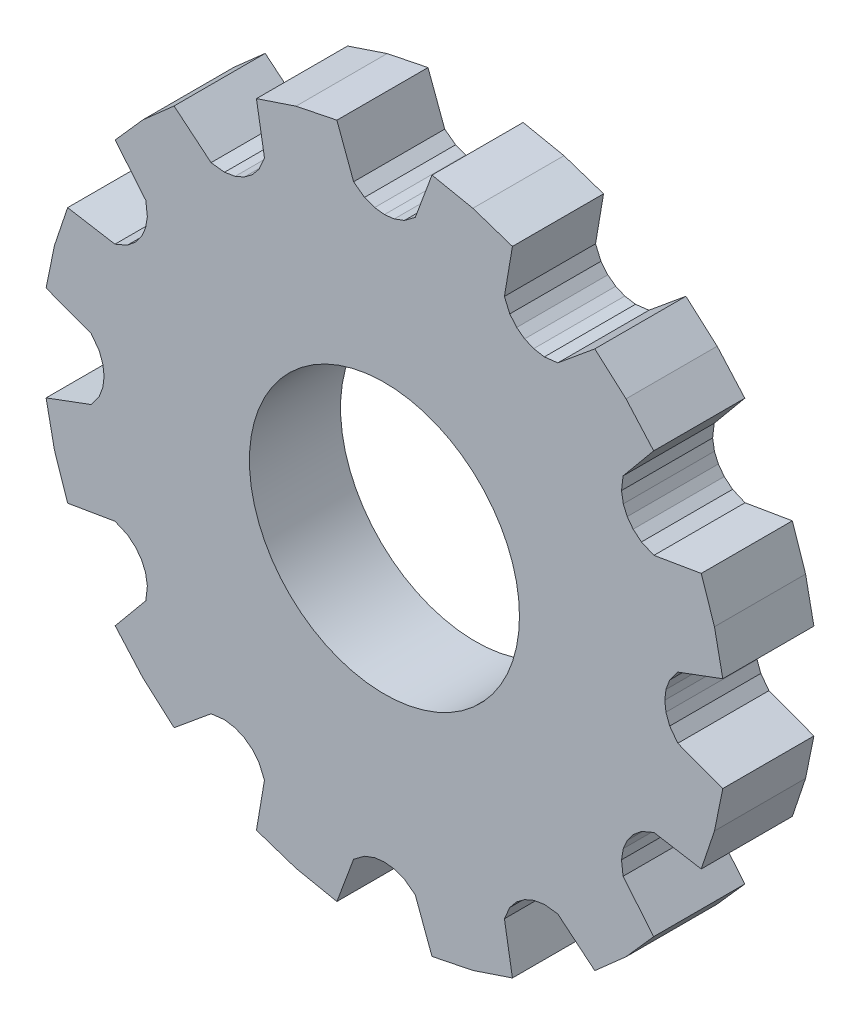
SolidWorks part; units mm, degrees
ref_plane "前视基准面" through (0, 0, 0) normal (0, 0, 1) x (1, 0, 0)
ref_plane "上视基准面" through (0, 0, 0) normal (0, 1, 0) x (1, 0, 0)
ref_plane "右视基准面" through (0, 0, 0) normal (1, 0, 0) x (0, 0, -1)
other "Configuration Table"
sketch "草图1" plane through (0, 0, 0) normal (0, 0, 1) x (1, 0, 0)
  line L0 (19.9192, -5.3373) -> (20.4212, -2.87)
  line L1 (20.4212, -2.87) -> (17.7062, -1.861)
  line L2 (17.7062, -1.861) -> (17.2174, -1.204)
  line L3 (17.2174, -1.204) -> (16.9905, -0.5933)
  line L4 (16.9905, -0.5933) -> (16.9219, 0)
  line L5 (16.9219, 0) -> (16.9905, 0.5933)
  line L6 (16.9905, 0.5933) -> (17.2174, 1.204)
  line L7 (17.2174, 1.204) -> (17.7062, 1.861)
  line L8 (17.7062, 1.861) -> (20.4212, 2.87)
  line L9 (20.4212, 2.87) -> (19.9192, 5.3373)
  line L10 (19.9192, 5.3373) -> (19.1203, 7.7251)
  line L11 (19.1203, 7.7251) -> (16.2645, 7.2414)
  line L12 (16.2645, 7.2414) -> (15.5127, 7.5661)
  line L13 (15.5127, 7.5661) -> (15.0108, 7.9814)
  line L14 (15.0108, 7.9814) -> (14.6548, 8.4609)
  line L15 (14.6548, 8.4609) -> (14.4175, 9.0091)
  line L16 (14.4175, 9.0091) -> (14.3087, 9.6514)
  line L17 (14.3087, 9.6514) -> (14.4035, 10.4648)
  line L18 (14.4035, 10.4648) -> (16.2503, 12.6961)
  line L19 (16.2503, 12.6961) -> (14.5819, 14.5819)
  line L20 (14.5819, 14.5819) -> (12.6961, 16.2503)
  line L21 (12.6961, 16.2503) -> (10.4648, 14.4035)
  line L22 (10.4648, 14.4035) -> (9.6514, 14.3087)
  line L23 (9.6514, 14.3087) -> (9.0091, 14.4175)
  line L24 (9.0091, 14.4175) -> (8.4609, 14.6548)
  line L25 (8.4609, 14.6548) -> (7.9814, 15.0108)
  line L26 (7.9814, 15.0108) -> (7.5661, 15.5127)
  line L27 (7.5661, 15.5127) -> (7.2414, 16.2645)
  line L28 (7.2414, 16.2645) -> (7.7251, 19.1203)
  line L29 (7.7251, 19.1203) -> (5.3373, 19.9192)
  line L30 (5.3373, 19.9192) -> (2.87, 20.4212)
  line L31 (2.87, 20.4212) -> (1.861, 17.7062)
  line L32 (1.861, 17.7062) -> (1.204, 17.2174)
  line L33 (1.204, 17.2174) -> (0.5933, 16.9905)
  line L34 (0.5933, 16.9905) -> (0, 16.9219)
  line L35 (0, 16.9219) -> (-0.5933, 16.9905)
  line L36 (-0.5933, 16.9905) -> (-1.204, 17.2174)
  line L37 (-1.204, 17.2174) -> (-1.861, 17.7062)
  line L38 (-1.861, 17.7062) -> (-2.87, 20.4212)
  line L39 (-2.87, 20.4212) -> (-5.3373, 19.9192)
  line L40 (-5.3373, 19.9192) -> (-7.7251, 19.1203)
  line L41 (-7.7251, 19.1203) -> (-7.2414, 16.2645)
  line L42 (-7.2414, 16.2645) -> (-7.5661, 15.5127)
  line L43 (-7.5661, 15.5127) -> (-7.9814, 15.0108)
  line L44 (-7.9814, 15.0108) -> (-8.4609, 14.6548)
  line L45 (-8.4609, 14.6548) -> (-9.0091, 14.4175)
  line L46 (-9.0091, 14.4175) -> (-9.6514, 14.3087)
  line L47 (-9.6514, 14.3087) -> (-10.4648, 14.4035)
  line L48 (-10.4648, 14.4035) -> (-12.6961, 16.2503)
  line L49 (-12.6961, 16.2503) -> (-14.5819, 14.5819)
  line L50 (-14.5819, 14.5819) -> (-16.2503, 12.6961)
  line L51 (-16.2503, 12.6961) -> (-14.4035, 10.4648)
  line L52 (-14.4035, 10.4648) -> (-14.3087, 9.6514)
  line L53 (-14.3087, 9.6514) -> (-14.4175, 9.0091)
  line L54 (-14.4175, 9.0091) -> (-14.6548, 8.4609)
  line L55 (-14.6548, 8.4609) -> (-15.0108, 7.9814)
  line L56 (-15.0108, 7.9814) -> (-15.5127, 7.5661)
  line L57 (-15.5127, 7.5661) -> (-16.2645, 7.2414)
  line L58 (-16.2645, 7.2414) -> (-19.1203, 7.7251)
  line L59 (-19.1203, 7.7251) -> (-19.9192, 5.3373)
  line L60 (-19.9192, 5.3373) -> (-20.4212, 2.87)
  line L61 (-20.4212, 2.87) -> (-17.7062, 1.861)
  line L62 (-17.7062, 1.861) -> (-17.2174, 1.204)
  line L63 (-17.2174, 1.204) -> (-16.9905, 0.5933)
  line L64 (-16.9905, 0.5933) -> (-16.9219, 0)
  line L65 (-16.9219, 0) -> (-16.9905, -0.5933)
  line L66 (-16.9905, -0.5933) -> (-17.2174, -1.204)
  line L67 (-17.2174, -1.204) -> (-17.7062, -1.861)
  line L68 (-17.7062, -1.861) -> (-20.4212, -2.87)
  line L69 (-20.4212, -2.87) -> (-19.9192, -5.3373)
  line L70 (-19.9192, -5.3373) -> (-19.1203, -7.7251)
  line L71 (-19.1203, -7.7251) -> (-16.2645, -7.2414)
  line L72 (-16.2645, -7.2414) -> (-15.5127, -7.5661)
  line L73 (-15.5127, -7.5661) -> (-15.0108, -7.9814)
  line L74 (-15.0108, -7.9814) -> (-14.6548, -8.4609)
  line L75 (-14.6548, -8.4609) -> (-14.4175, -9.0091)
  line L76 (-14.4175, -9.0091) -> (-14.3087, -9.6514)
  line L77 (-14.3087, -9.6514) -> (-14.4035, -10.4648)
  line L78 (-14.4035, -10.4648) -> (-16.2503, -12.6961)
  line L79 (-16.2503, -12.6961) -> (-14.5819, -14.5819)
  line L80 (-14.5819, -14.5819) -> (-12.6961, -16.2503)
  line L81 (-12.6961, -16.2503) -> (-10.4648, -14.4035)
  line L82 (-10.4648, -14.4035) -> (-9.6514, -14.3087)
  line L83 (-9.6514, -14.3087) -> (-9.0091, -14.4175)
  line L84 (-9.0091, -14.4175) -> (-8.4609, -14.6548)
  line L85 (-8.4609, -14.6548) -> (-7.9814, -15.0108)
  line L86 (-7.9814, -15.0108) -> (-7.5661, -15.5127)
  line L87 (-7.5661, -15.5127) -> (-7.2414, -16.2645)
  line L88 (-7.2414, -16.2645) -> (-7.7251, -19.1203)
  line L89 (-7.7251, -19.1203) -> (-5.3373, -19.9192)
  line L90 (-5.3373, -19.9192) -> (-2.87, -20.4212)
  line L91 (-2.87, -20.4212) -> (-1.861, -17.7062)
  line L92 (-1.861, -17.7062) -> (-1.204, -17.2174)
  line L93 (-1.204, -17.2174) -> (-0.5933, -16.9905)
  line L94 (-0.5933, -16.9905) -> (0, -16.9219)
  line L95 (0, -16.9219) -> (0.5933, -16.9905)
  line L96 (0.5933, -16.9905) -> (1.204, -17.2174)
  line L97 (1.204, -17.2174) -> (1.861, -17.7062)
  line L98 (1.861, -17.7062) -> (2.87, -20.4212)
  line L99 (2.87, -20.4212) -> (5.3373, -19.9192)
  line L100 (5.3373, -19.9192) -> (7.7251, -19.1203)
  line L101 (7.7251, -19.1203) -> (7.2414, -16.2645)
  line L102 (7.2414, -16.2645) -> (7.5661, -15.5127)
  line L103 (7.5661, -15.5127) -> (7.9814, -15.0108)
  line L104 (7.9814, -15.0108) -> (8.4609, -14.6548)
  line L105 (8.4609, -14.6548) -> (9.0091, -14.4175)
  line L106 (9.0091, -14.4175) -> (9.6514, -14.3087)
  line L107 (9.6514, -14.3087) -> (10.4648, -14.4035)
  line L108 (10.4648, -14.4035) -> (12.6961, -16.2503)
  line L109 (12.6961, -16.2503) -> (14.5819, -14.5819)
  line L110 (14.5819, -14.5819) -> (16.2503, -12.6961)
  line L111 (16.2503, -12.6961) -> (14.4035, -10.4648)
  line L112 (14.4035, -10.4648) -> (14.3087, -9.6514)
  line L113 (14.3087, -9.6514) -> (14.4175, -9.0091)
  line L114 (14.4175, -9.0091) -> (14.6548, -8.4609)
  line L115 (14.6548, -8.4609) -> (15.0108, -7.9814)
  line L116 (15.0108, -7.9814) -> (15.5127, -7.5661)
  line L117 (15.5127, -7.5661) -> (16.2645, -7.2414)
  line L118 (16.2645, -7.2414) -> (19.1203, -7.7251)
  line L119 (19.1203, -7.7251) -> (19.9192, -5.3373)
extrude "Roller_seating_tooth_profile" add sketch "草图1" along normal blind 5.5
sketch "草图2" plane through (0, 0, 5.5) normal (0, 0, 1) x (1, 0, 0)
  circle A0 centre (0, 0) radius 8.15
  dimension "diameter" = 16.3
extrude "Through_shaft_bore" cut sketch "草图2" against normal through all
